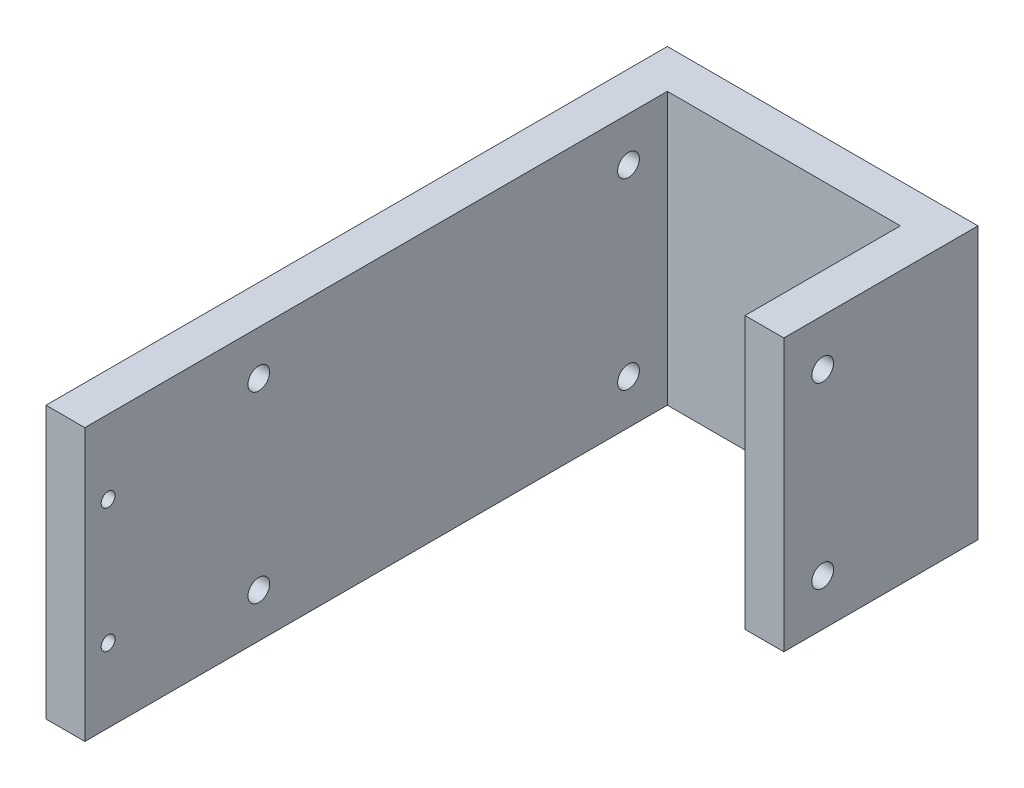
SolidWorks part; units mm, degrees
ref_plane "Front Plane" through (0, 0, 0) normal (0, 0, 1) x (1, 0, 0)
ref_plane "Top Plane" through (0, 0, 0) normal (0, 1, 0) x (1, 0, 0)
ref_plane "Right Plane" through (0, 0, 0) normal (1, 0, 0) x (0, 0, -1)
sketch "Sketch1" plane through (0, 0, 0) normal (0, 1, 0) x (1, 0, 0)
  line L1 (0, 0) -> (5, 0)
  line L2 (0, 0) -> (0, -80)
  line L3 (0, -80) -> (5, -80)
  line L4 (5, -5) -> (5, -80)
  line L5 (5, 0) -> (40, 0)
  line L7 (5, -5) -> (35, -5)
  line L8 (40, 0) -> (40, -5)
  line L10 (40, -5) -> (40, -25)
  line L11 (40, -25) -> (35, -25)
  line L12 (35, -5) -> (35, -25)
  dimension "D1" = 5
  dimension "D2" = 30
  dimension "D3" = 80
  dimension "D4" = 5
  dimension "D5" = 25
extrude "Boss-Extrude1" add sketch "Sketch1" along normal blind 35
sketch "Sketch3" plane through (40, 0, 0) normal (1, 0, 0) x (0, 0, -1)
  line L0 (-20, 35) -> (-20, 29) construction
  line L1 (-25, 35) -> (0, 35) construction
  line L2 (-20, 29) -> (-20, 6) construction
  line L3 (-20, 6) -> (-20, 0) construction
  line L4 (-25, 0) -> (0, 0) construction
  line L6 (0, 35) -> (0, 0) construction
  circle A0 centre (-20, 29) radius 1.4
  circle A1 centre (-20, 6) radius 1.4
  dimension "D3" = 2.8
  dimension "D1" = 20
  dimension "D2" = 23
extrude "Cut-Extrude1" cut sketch "Sketch3" against normal up to surface (5 mm away) up to face at (35, 17.5, 15)
sketch "Sketch4" plane through (0, 0, 0) normal (-1, 0, 0) x (0, 0, 1)
  line L0 (0, 29.3) -> (10, 29.3) construction
  line L1 (0, 35) -> (0, 0) construction
  line L2 (0, 29.3) -> (0, 35) construction
  line L3 (10, 29.3) -> (57.6, 29.3) construction
  line L4 (10, 29.3) -> (10, 5.7) construction
  line L5 (10, 5.7) -> (57.6, 5.7) construction
  line L6 (57.6, 29.3) -> (57.6, 5.7) construction
  line L7 (10, 5.7) -> (0, 5.7) construction
  line L8 (0, 5.7) -> (0, 0) construction
  circle A0 centre (10, 29.3) radius 1.4
  circle A1 centre (57.6, 29.3) radius 1.4
  circle A2 centre (57.6, 5.7) radius 1.4
  circle A3 centre (10, 5.7) radius 1.4
  dimension "D4" = 2.8
  dimension "D1" = 23.6
  dimension "D2" = 47.6
  dimension "D3" = 10
extrude "Cut-Extrude2" cut sketch "Sketch4" against normal up to surface (5 mm away) up to face at (5, 17.5, 42.5)
sketch "Sketch5" plane through (0, 0, 0) normal (-1, 0, 0) x (0, 0, 1)
  line L0 (0, 35) -> (80, 35) construction
  line L1 (2, 33) -> (78, 33) construction
  line L2 (2, 33) -> (2, 2) construction
  line L3 (2, 2) -> (78, 2) construction
  line L4 (78, 33) -> (78, 2) construction
  line L5 (0, 35) -> (0, 0) construction
  line L6 (0, 0) -> (80, 0) construction
  line L7 (80, 35) -> (80, 0) construction
  line L9 (1.3053, 33.9937) -> (0.7921, 32.8952)
  line L10 (0.7921, 32.8952) -> (1.4868, 31.9015)
  line L11 (1.4868, 31.9015) -> (2.6947, 32.0063)
  line L12 (2.6947, 32.0063) -> (3.2079, 33.1048)
  line L13 (3.2079, 33.1048) -> (2.5132, 34.0985)
  line L14 (2.5132, 34.0985) -> (1.3053, 33.9937)
  line L15 (2.6145, 3.0452) -> (1.4021, 3.0548)
  line L16 (1.4021, 3.0548) -> (0.7876, 2.0096)
  line L17 (0.7876, 2.0096) -> (1.3855, 0.9548)
  line L18 (1.3855, 0.9548) -> (2.5979, 0.9452)
  line L19 (2.5979, 0.9452) -> (3.2124, 1.9904)
  line L20 (3.2124, 1.9904) -> (2.6145, 3.0452)
  line L21 (78.9573, 2.7441) -> (77.8343, 3.2011)
  line L22 (77.8343, 3.2011) -> (76.877, 2.457)
  line L23 (76.877, 2.457) -> (77.0427, 1.2559)
  line L24 (77.0427, 1.2559) -> (78.1657, 0.7989)
  line L25 (78.1657, 0.7989) -> (79.123, 1.543)
  line L26 (79.123, 1.543) -> (78.9573, 2.7441)
  line L27 (78.7407, 33.9599) -> (77.5391, 34.1214)
  line L28 (77.5391, 34.1214) -> (76.7984, 33.1616)
  line L29 (76.7984, 33.1616) -> (77.2593, 32.0401)
  line L30 (77.2593, 32.0401) -> (78.4609, 31.8786)
  line L31 (78.4609, 31.8786) -> (79.2016, 32.8384)
  line L32 (79.2016, 32.8384) -> (78.7407, 33.9599)
  circle A0 centre (2, 33) radius 1.05 construction
  circle A1 centre (2, 2) radius 1.05 construction
  circle A2 centre (78, 2) radius 1.05 construction
  circle A3 centre (78, 33) radius 1.05 construction
  dimension "D5" = 2.1
  dimension "D1" = 2
  dimension "D2" = 2
  dimension "D3" = 2
  dimension "D4" = 2
extrude "Cut-Extrude3" cut sketch "Sketch5" against normal blind 2.3
sketch "Sketch6" plane through (0, 0, 0) normal (-1, 0, 0) x (0, 0, 1)
  line L0 (80, 25.5) -> (77, 25.5) construction
  line L1 (80, 35) -> (80, 0) construction
  line L2 (77, 25.5) -> (77, 9.5) construction
  line L3 (77, 9.5) -> (80, 9.5) construction
  line L4 (80, 25.5) -> (80, 35) construction
  line L5 (77, 25.5) -> (65.1536, 25.5) construction
  line L6 (77, 25.5) -> (77, 9.5) construction
  line L7 (77, 9.5) -> (65.1536, 9.5) construction
  line L8 (65.1536, 25.5) -> (65.1536, 9.5) construction
  line L9 (80, 9.5) -> (80, 0) construction
  circle A0 centre (77, 25.5) radius 0.9
  circle A1 centre (77, 9.5) radius 0.9
  dimension "D3" = 1.8
  dimension "D1" = 16
  dimension "D2" = 3
extrude "Cut-Extrude4" cut sketch "Sketch6" against normal up to surface (5 mm away) up to face at (5, 5.7, 11.4)
